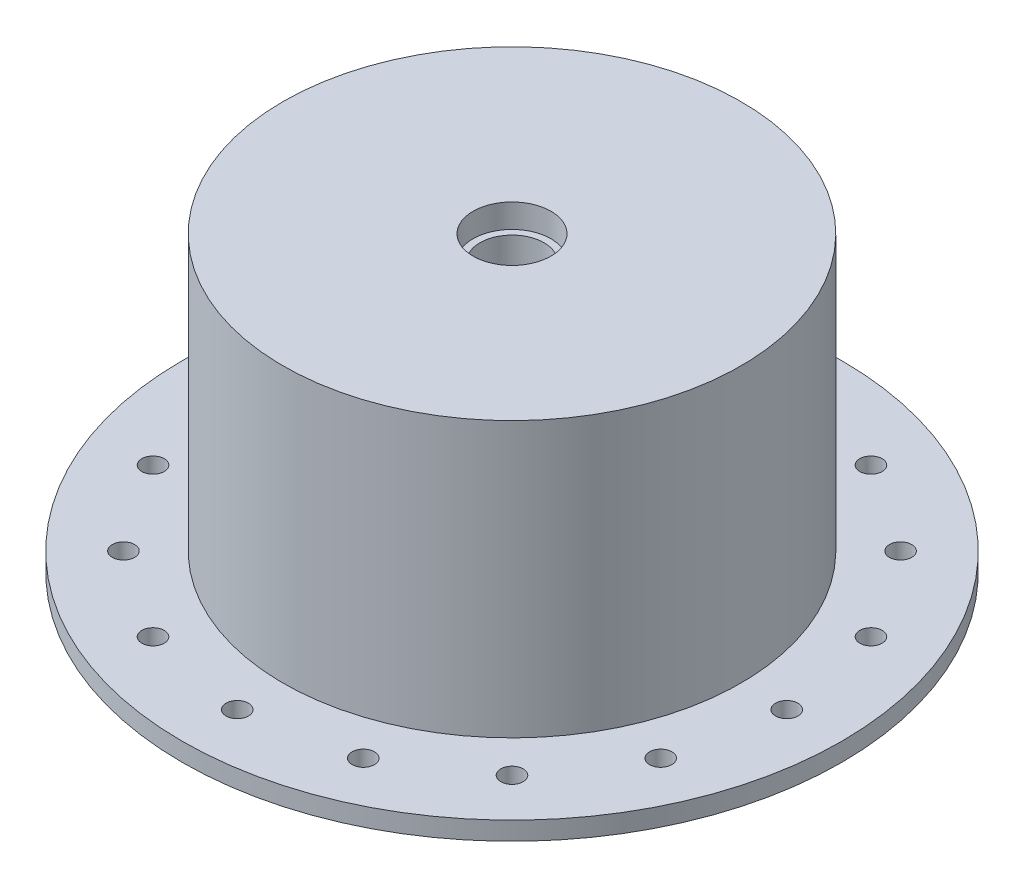
SolidWorks part; units mm, degrees
ref_plane "Front Plane" through (0, 0, 0) normal (0, 0, 1) x (1, 0, 0)
ref_plane "Top Plane" through (0, 0, 0) normal (0, 1, 0) x (1, 0, 0)
ref_plane "Right Plane" through (0, 0, 0) normal (1, 0, 0) x (0, 0, -1)
sketch "Sketch1" plane through (0, 0, 0) normal (0, 0, 1) x (1, 0, 0)
  line L0 (-21.25, -80) -> (-21.25, -67)
  line L1 (0, 80) -> (-0.2735, 80)
  line L2 (-180, 80) -> (-180, 70) construction
  line L3 (-180, 70) -> (-125, 70) construction
  line L4 (0, 80) -> (0, -80) construction
  line L6 (-125, 70) -> (-125, -70)
  line L7 (126.8971, -70) -> (-123.1029, -70) construction
  line L8 (-125, -70) -> (-180, -70)
  line L9 (-180, -70) -> (-180, -80)
  line L10 (-180, -80) -> (-42.5, -80)
  line L11 (-21.25, -67) -> (-17.5, -67)
  line L12 (-42.5, 80) -> (-42.5, -80) construction
  line L13 (-42.5, -80) -> (0, -80) construction
  line L14 (-42.5, -80) -> (-21.25, -80)
  line L15 (-0.2735, 80) -> (-42.5, 80) construction
  line L16 (-42.5, 80) -> (-125, 80)
  line L17 (-125, 70) -> (-125, 80)
  line L18 (-125, 80) -> (-180, 80) construction
  line L19 (-17.5, -67) -> (-17.5, 67)
  line L20 (-17.5, -67) -> (0, -67) construction
  line L21 (0, 0) -> (-193.1236, 0) construction
  line L22 (-21.25, 80) -> (-21.25, 67)
  line L23 (-21.25, 67) -> (-17.5, 67)
  line L24 (-21.25, 80) -> (-42.5, 80)
  point P1 (0, 0)
  dimension "D1" = 10
  dimension "D2" = 10
  dimension "D3" = 250
  dimension "D4" = 160
  dimension "D5" = 360
  dimension "D6" = 42.5
  dimension "D7" = 13
  dimension "D8" = 42.5
  dimension "D9" = 35
revolve "Revolve1" add sketch "Sketch1" angle 360 about L4
sketch "Sketch2" plane through (0, -70, 0) normal (0, 1, 0) x (1, 0, 0)
  line L0 (0, 0) -> (0, 198.2396) construction
  circle A0 centre (0, 150) radius 6.1
  circle A1 centre (57.4025, 138.5819) radius 6.1
  circle A2 centre (106.066, 106.066) radius 6.1
  circle A3 centre (138.5819, 57.4025) radius 6.1
  circle A4 centre (150, 0) radius 6.1
  circle A5 centre (138.5819, -57.4025) radius 6.1
  circle A6 centre (106.066, -106.066) radius 6.1
  circle A7 centre (57.4025, -138.5819) radius 6.1
  circle A8 centre (0, -150) radius 6.1
  circle A9 centre (-57.4025, -138.5819) radius 6.1
  circle A10 centre (-106.066, -106.066) radius 6.1
  circle A11 centre (-138.5819, -57.4025) radius 6.1
  circle A12 centre (-150, 0) radius 6.1
  circle A13 centre (-138.5819, 57.4025) radius 6.1
  circle A14 centre (-106.066, 106.066) radius 6.1
  circle A15 centre (-57.4025, 138.5819) radius 6.1
  point P53 (0, 0)
  dimension "D1" = 12.2
  dimension "D2" = 150
  dimension "D3" = 16
extrude "Cut-Extrude1" cut sketch "Sketch2" against normal through all both and the other way through all
